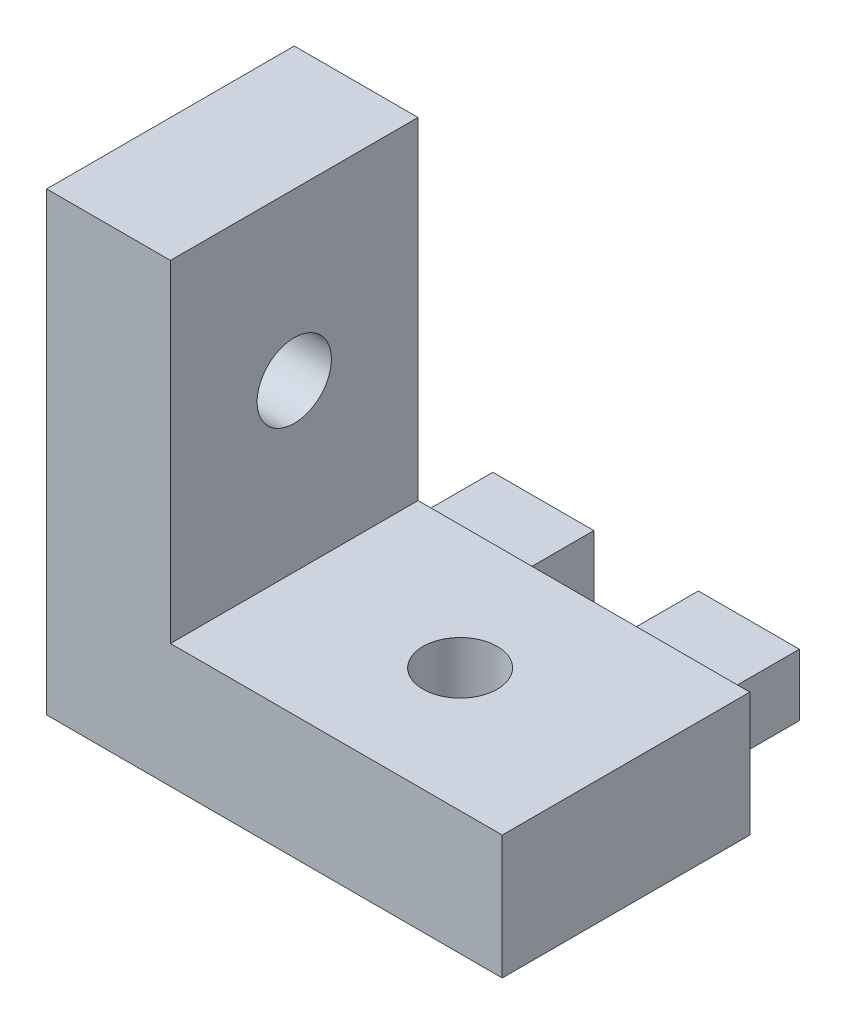
SolidWorks part; units mm, degrees
ref_plane "Front Plane" through (0, 0, 0) normal (0, 0, 1) x (1, 0, 0)
ref_plane "Top Plane" through (0, 0, 0) normal (0, 1, 0) x (1, 0, 0)
ref_plane "Right Plane" through (0, 0, 0) normal (1, 0, 0) x (0, 0, -1)
sketch "Sketch1" plane through (0, 0, 0) normal (0, 0, 1) x (1, 0, 0)
  line L0 (-0.7576, 12.5288) -> (-5.7576, 12.5288)
  line L1 (-5.7576, 12.5288) -> (-5.7576, -5.8712)
  line L2 (-5.7576, -5.8712) -> (12.6424, -5.8712)
  line L3 (12.6424, -5.8712) -> (12.6424, -0.8712)
  line L4 (12.6424, -0.8712) -> (-0.7576, -0.8712)
  line L5 (-0.7576, -0.8712) -> (-0.7576, 12.5288)
  point P2 (-1.204, 4.2045)
  dimension "D1" = 5
  dimension "D2" = 13.4
extrude "Boss-Extrude1" add sketch "Sketch1" along normal blind 10
sketch "Sketch2" plane through (0, -0.8712, 0) normal (0, 1, 0) x (1, 0, 0)
  line L0 (12.6424, -10) -> (12.6424, 0) construction
  line L1 (12.6424, 0) -> (-0.7576, 0) construction
  circle A0 centre (5.9424, -5) radius 1.5
  point P2 (0, 0)
  point P5 (12.6424, -5)
  point P8 (5.9424, 0)
  dimension "D1" = 3
extrude "Cut-Extrude1" cut sketch "Sketch2" against normal up to next
sketch "Sketch3" plane through (-0.7576, 0, 0) normal (1, 0, 0) x (0, 0, -1)
  line L0 (0, -0.8712) -> (0, 12.5288) construction
  line L1 (-10, 12.5288) -> (0, 12.5288) construction
  circle A0 centre (-5, 5.8288) radius 1.5
  point P4 (0, 0)
  point P5 (0, 5.8288)
  point P8 (-5, 12.5288)
  dimension "D1" = 3
extrude "Cut-Extrude2" cut sketch "Sketch3" against normal up to next
sketch "Sketch4" plane through (0, -5.8712, 0) normal (0, -1, 0) x (1, 0, 0)
  line L1 (5.5651, -5) -> (9.6424, -5)
  line L2 (5.5651, -5) -> (5.5651, 0)
  line L3 (5.5651, 0) -> (9.6424, 0)
  line L4 (9.6424, -5) -> (9.6424, 0)
  line L5 (-2.7376, -5) -> (1.3424, -5)
  line L6 (-2.7376, -5) -> (-2.7376, 0)
  line L7 (-2.7376, 0) -> (1.3424, 0)
  line L8 (1.3424, -5) -> (1.3424, 0)
  line L9 (1.3424, 0) -> (1.3424, -200) construction
  line L10 (5.5651, 0) -> (5.5651, -200) construction
  line L11 (9.6424, 0) -> (9.6424, -200) construction
  line L12 (-5.7576, 0) -> (12.6424, 0) construction
  dimension "D1" = 4.08
  dimension "D2" = 5
extrude "Boss-Extrude2" add sketch "Sketch4" against normal blind 2.5
